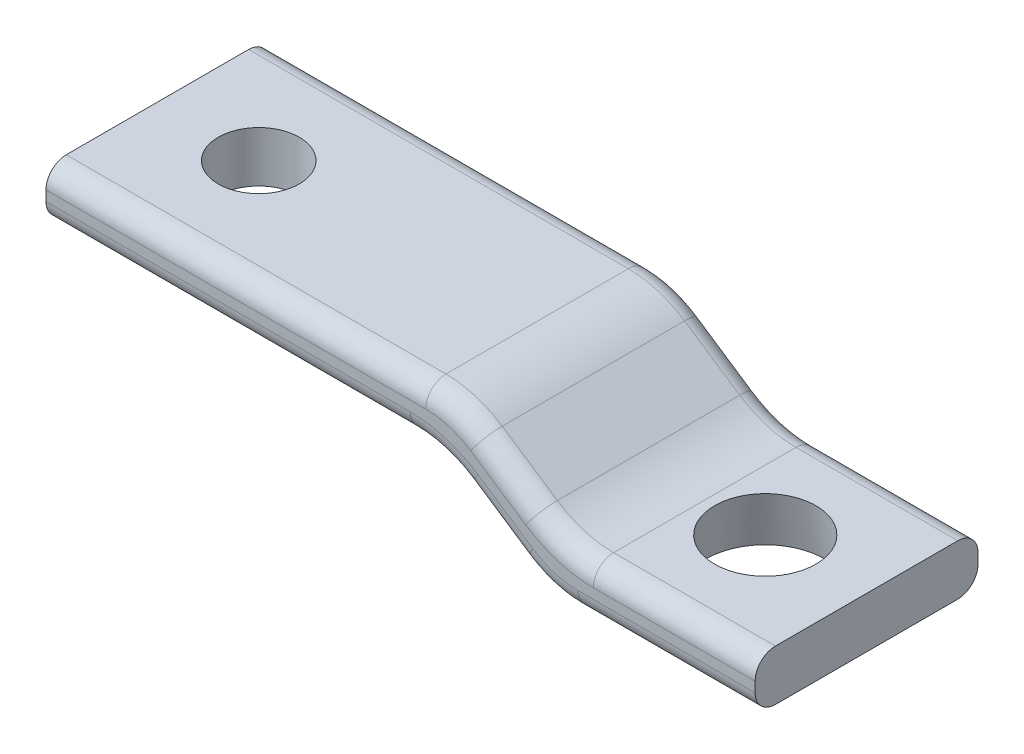
SolidWorks part; units mm, degrees
material "Acier galvanisé"
ref_plane "Plan de face" through (0, 0, 0) normal (0, 0, 1) x (1, 0, 0)
ref_plane "Plan de dessus" through (0, 0, 0) normal (0, 1, 0) x (1, 0, 0)
ref_plane "Plan de droite" through (0, 0, 0) normal (1, 0, 0) x (0, 0, -1)
sketch "Esquisse1" plane through (0, 0, 0) normal (0, 0, 1) x (1, 0, 0)
  line L0 (0, 0) -> (37.4842, 0)
  line L1 (43.037, -1.6833) -> (48.4788, -5.3167)
  line L2 (54.0315, -7) -> (70, -7)
  line L3 (52.5158, -12) -> (70, -12)
  line L4 (41.5212, -6.6833) -> (46.963, -10.3167)
  line L5 (0, -5) -> (35.9685, -5)
  line L6 (0, 0) -> (0, -5)
  line L7 (70, -7) -> (70, -12)
  arc A0 (43.037, -1.6833) -> (37.4842, 0) centre (37.4842, -10) ccw
  arc A1 (41.5212, -6.6833) -> (35.9685, -5) centre (35.9685, -15) ccw
  arc A2 (52.5158, -12) -> (46.963, -10.3167) centre (52.5158, -2) cw
  arc A3 (54.0315, -7) -> (48.4788, -5.3167) centre (54.0315, 3) cw
  point P13 (39, -5)
  point P18 (51, -7)
  dimension "D6" = 10
  dimension "D2" = 39
  dimension "D3" = 19
  dimension "D4" = 70
  dimension "D5" = 12
  dimension "D1" = 5
extrude "Extrusion1" add sketch "Esquisse1" along normal mid plane 22
fillet "Congé2" radius 2 20 edges at (62.0158, -7, -11) (51.1304, -6.5699, -11) (45.7579, -3.5, -11) (40.3854, -0.4301, -11) (18.7421, 0, -11) (61.2579, -12, 11) (49.6146, -11.5699, 11) (44.2421, -8.5, 11) (38.8696, -5.4301, 11) (62.0158, -7, 11) (51.1304, -6.5699, 11) (45.7579, -3.5, 11) (40.3854, -0.4301, 11) (61.2579, -12, -11) (49.6146, -11.5699, -11) (44.2421, -8.5, -11) (38.8696, -5.4301, -11) (17.9842, -5, 11) (18.7421, 0, 11) (17.9842, -5, -11)
sketch "Esquisse2" plane through (0, 0, 0) normal (0, 1, 0) x (-1, 0, 0)
  line L0 (0, 0) -> (-34.713, 0) construction
  line L1 (0, 9) -> (0, -9) construction
  circle A0 centre (-10, 0) radius 4
  dimension "D1" = 8
  dimension "D2" = 10
extrude "Enlèv. mat.-Extru.1" cut sketch "Esquisse2" against normal through all
sketch "Esquisse3" plane through (0, 0, 0) normal (0, 0, 1) x (1, 0, 0)
  line L0 (60, 1.9839) -> (60, -18.4194) construction
  line L1 (70, -9) -> (70, -7) construction
  line L2 (65, -7) -> (65.8816, -12)
  line L3 (54.0315, -7) -> (70, -7) construction
  line L4 (70, -12) -> (52.5158, -12) construction
  line L5 (65.8816, -12) -> (60, -12)
  line L6 (60, -12) -> (60, -7)
  line L7 (60, -7) -> (65, -7)
  dimension "D1" = 10
  dimension "D2" = 10
  dimension "D3" = 5
revolve "Enlèvement de matière-Révolution1" cut sketch "Esquisse3" angle 360 about L0
